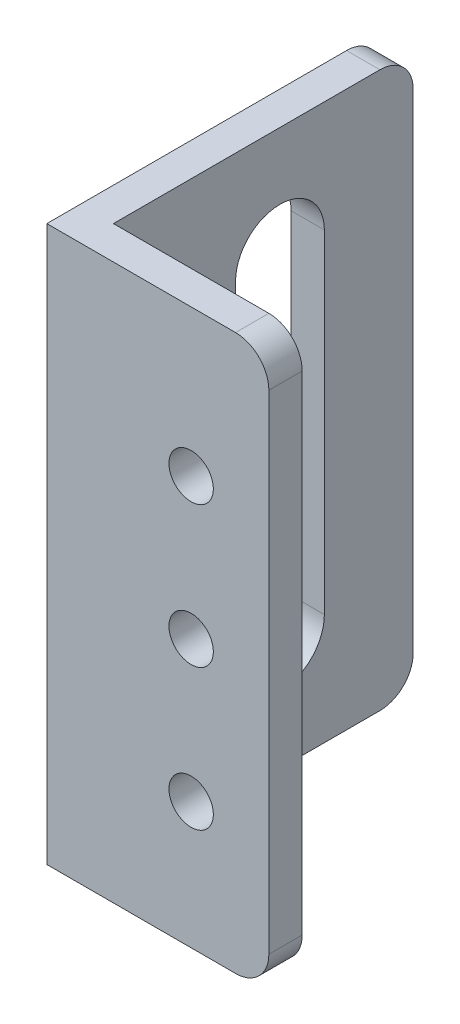
SolidWorks part; units mm, degrees
ref_plane "前视基准面" through (0, 0, 0) normal (0, 0, 1) x (1, 0, 0)
ref_plane "上视基准面" through (0, 0, 0) normal (0, 1, 0) x (1, 0, 0)
ref_plane "右视基准面" through (0, 0, 0) normal (1, 0, 0) x (0, 0, -1)
sketch "草图1" plane through (0, 0, 0) normal (0, 1, 0) x (1, 0, 0)
  line L2 (-1.5, 15) -> (1.5, 15)
  line L3 (-1.5, 15) -> (-1.5, -15)
  line L4 (-1.5, -15) -> (1.5, -15)
  line L5 (1.5, 15) -> (1.5, -15)
  line L6 (-1.5, 15) -> (1.5, -15) construction
  line L7 (-1.5, -15) -> (1.5, 15) construction
  line L8 (-1.5, -15) -> (18.5, -15)
  line L9 (-1.5, -15) -> (-1.5, -12)
  line L10 (-1.5, -12) -> (18.5, -12)
  line L11 (18.5, -15) -> (18.5, -12)
  point P2 (0, 0)
  dimension "D1" = 3
  dimension "D2" = 3
  dimension "D3" = 30
  dimension "D4" = 20
extrude "凸台-拉伸1" add sketch "草图1" along normal blind 50 contours L3 L10 L5 L2 | L10 L3 L4 L5 | L8 L11 L10 L5
sketch "草图2" plane through (0, 0, 15) normal (0, 0, 1) x (1, 0, 0)
  line L0 (11.5, 50) -> (11.5, 0) construction
  line L1 (-1.5, 50) -> (18.5, 50) construction
  line L3 (18.5, 50) -> (18.5, 0) construction
  circle A0 centre (11.5, 36.8) radius 2
  circle A2 centre (11.5, 24.1) radius 2
  circle A3 centre (11.5, 11.4) radius 2
  dimension "D1" = 4
  dimension "D2" = 13.2
  dimension "D4" = 12.7
  dimension "D5" = 7
  dimension "D3" = 3
extrude "切除-拉伸1" cut sketch "草图2" against normal blind 10
sketch "草图3" plane through (-1.5, 0, 0) normal (-1, 0, 0) x (0, 0, 1)
  line L0 (-3, 40) -> (-3, 10) construction
  line L1 (1, 40) -> (1, 10)
  line L2 (-7, 40) -> (-7, 10)
  line L4 (-15, 50) -> (-15, 0) construction
  line L5 (-15, 25) -> (15, 25) construction
  line L6 (15, 50) -> (15, 0) construction
  arc A0 (1, 40) -> (-7, 40) centre (-3, 40) ccw
  arc A1 (-7, 10) -> (1, 10) centre (-3, 10) ccw
  point P3 (-3, 25)
  dimension "D3" = 4
  dimension "D1" = 30
  dimension "D2" = 12
extrude "切除-拉伸2" cut sketch "草图3" against normal blind 10
fillet "圆角1" radius 3 4 edges at (0, 0, -15) (0, 50, -15) (18.5, 0, 13.5) (18.5, 50, 13.5)
